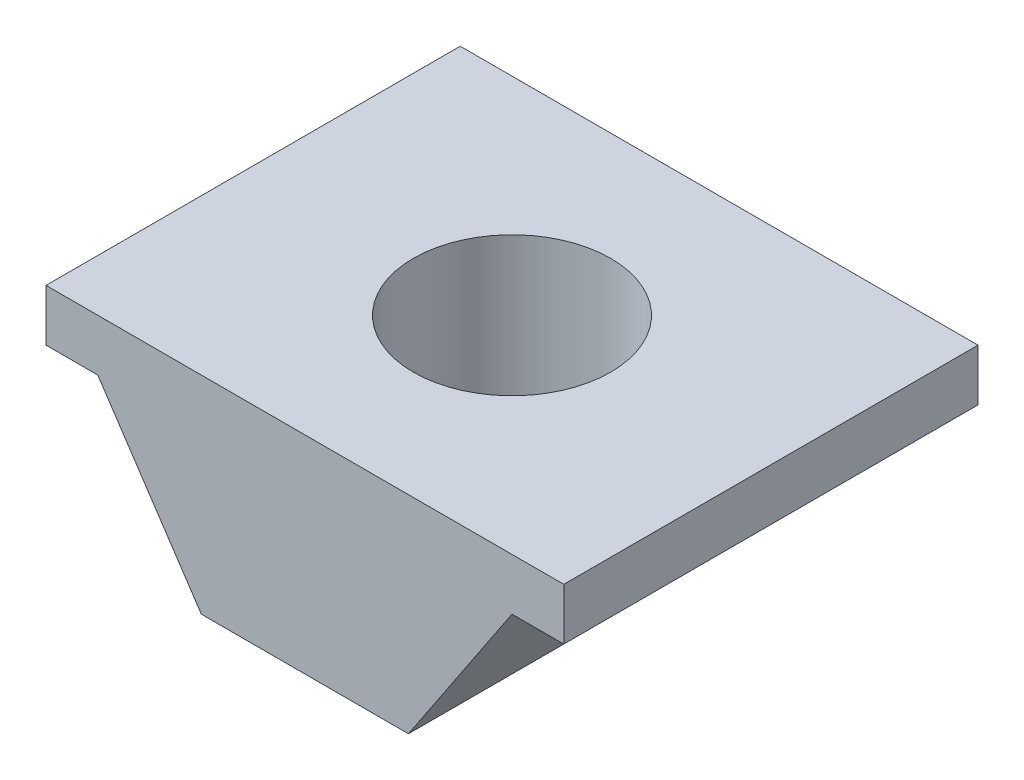
SolidWorks part; units mm, degrees
material "Aleación 6061"
ref_plane "Alzado" through (0, 0, 0) normal (0, 0, 1) x (1, 0, 0)
ref_plane "Planta" through (0, 0, 0) normal (0, 1, 0) x (1, 0, 0)
ref_plane "Vista lateral" through (0, 0, 0) normal (1, 0, 0) x (0, 0, -1)
sketch "Croquis1" plane through (0, 0, 0) normal (0, 0, 1) x (1, 0, 0)
  line L0 (0, 0) -> (25, 0)
  line L1 (25, 0) -> (25, -2.5)
  line L2 (25, -2.5) -> (22.5, -2.5)
  line L3 (0, 0) -> (0, -2.5)
  line L4 (0, -2.5) -> (2.5, -2.5)
  line L5 (2.5, -2.5) -> (7.5, -10)
  line L6 (7.5, -10) -> (17.5, -10)
  line L7 (17.5, -10) -> (22.5, -2.5)
  line L8 (12.5, -10) -> (12.5, 0) construction
  dimension "D1" = 25
  dimension "D2" = 10
  dimension "D3" = 2.5
  dimension "D4" = 10
  dimension "D5" = 2.5
extrude "Saliente-Extruir1" add sketch "Croquis1" along normal blind 20
sketch "Croquis2" plane through (0, 0, 0) normal (0, 1, 0) x (1, 0, 0)
  line L0 (12.5, 0) -> (12.5, -20) construction
  line L1 (25, 0) -> (0, 0) construction
  line L2 (25, -20) -> (0, -20) construction
  line L3 (0, -10) -> (25, -10) construction
  line L4 (0, -20) -> (0, 0) construction
  line L5 (25, -20) -> (25, 0) construction
  circle A0 centre (12.5, -10) radius 4.7625
  dimension "D1" = 9.525
extrude "Cortar-Extruir1" cut sketch "Croquis2" against normal up to vertex
